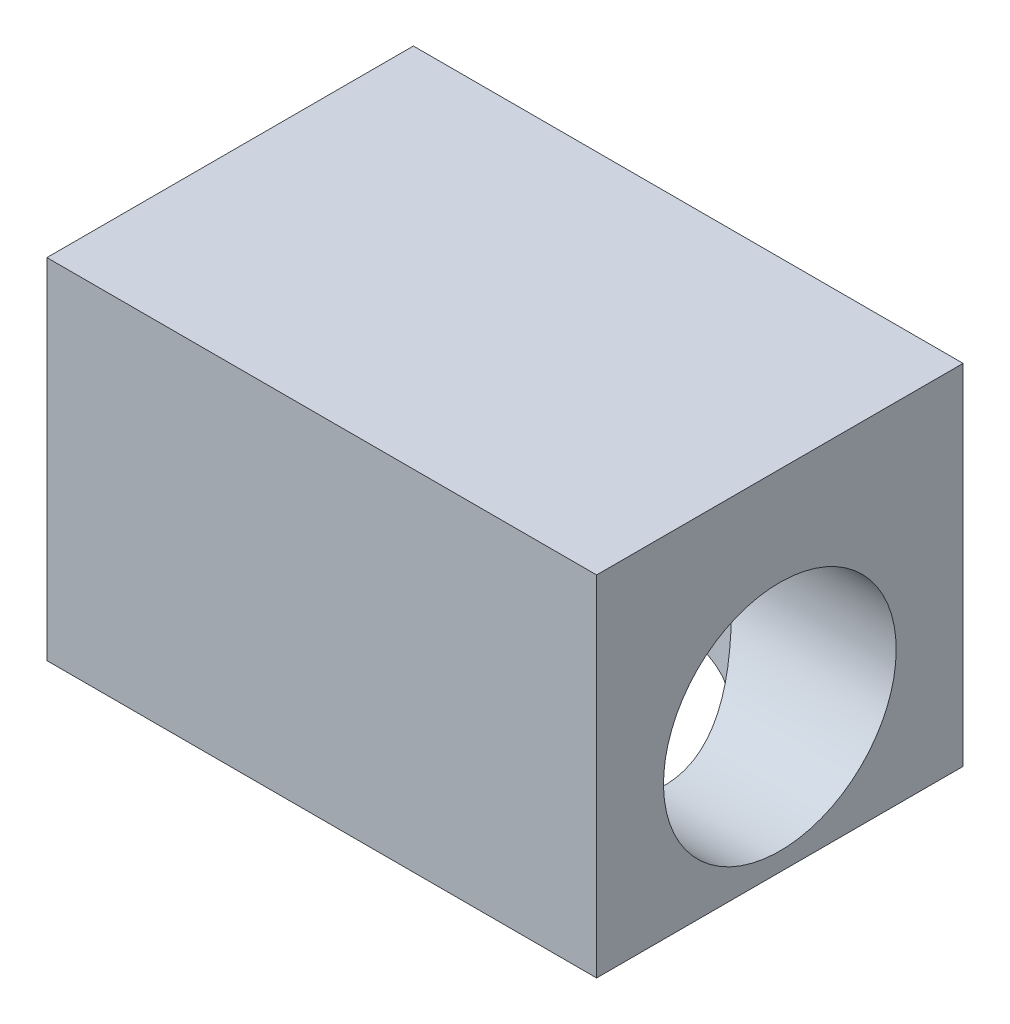
SolidWorks part; units mm, degrees
material "6061-T6 (SS)"
ref_plane "Front Plane" through (0, 0, 0) normal (0, 0, 1) x (1, 0, 0)
ref_plane "Top Plane" through (0, 0, 0) normal (0, 1, 0) x (1, 0, 0)
ref_plane "Right Plane" through (0, 0, 0) normal (1, 0, 0) x (0, 0, -1)
sketch "Sketch1" plane through (0, 0, 0) normal (0, 1, 0) x (1, 0, 0)
  line L1 (-30, 20) -> (30, 20)
  line L2 (-30, 20) -> (-30, -20)
  line L3 (-30, -20) -> (30, -20)
  line L4 (30, 20) -> (30, -20)
  line L5 (-30, 20) -> (30, -20) construction
  line L6 (-30, -20) -> (30, 20) construction
  point P0 (0, 0)
  dimension "D1" = 40
  dimension "D2" = 60
extrude "Boss-Extrude1" add sketch "Sketch1" against normal blind 38.1
sketch "Sketch2" plane through (0, 0, 0) normal (0, 0, 1) x (1, 0, 0)
  line L0 (62.6309, -36.1) -> (62.6309, -23.4)
  line L1 (62.6309, -23.4) -> (5, -23.4)
  line L2 (5, -23.4) -> (12.6309, -36.1)
  line L3 (12.6309, -36.1) -> (62.6309, -36.1)
  line L4 (0, 0) -> (0, -38.1) construction
  line L5 (-30, -38.1) -> (30, -38.1) construction
  line L6 (-12.6309, -36.1) -> (-5, -23.4)
  line L7 (-5, -23.4) -> (-62.6309, -23.4)
  line L8 (-62.6309, -23.4) -> (-62.6309, -36.1)
  line L9 (-62.6309, -36.1) -> (-12.6309, -36.1)
  line L10 (-5, -23.4) -> (5, -23.4) construction
  point P3 (37.6309, -36.1)
  point P10 (-13.5222, -2.3)
  point P11 (-5, -34.8708)
  point P16 (0, -23.4)
  point P17 (-11.2914, -2.3)
  point P18 (5, -17.5)
  point P19 (5, -20.6599)
  point P20 (-5, -34.9228)
  point P21 (-13.312, -35.9845)
  dimension "D1" = 12.7
  dimension "D2" = 121
  dimension "D3" = 10
  dimension "D4" = 50
  dimension "D5" = 2
revolve "Cut-Revolve1" cut sketch "Sketch2" angle 360 about L7
sketch "Sketch4" plane through (0, 0, 0) normal (0, 0, 1) x (1, 0, 0)
  line L0 (-17.5, -38.1) -> (-17.5, -11)
  line L1 (-30, -38.1) -> (30, -38.1) construction
  line L2 (-17.5, -11) -> (-13, -11)
  line L3 (-13, -11) -> (-13, -3)
  line L4 (-13, -3) -> (-11, -3)
  line L5 (-11, -3) -> (-11, -2)
  line L6 (-11, -2) -> (11, -2)
  line L7 (11, -2) -> (11, -3)
  line L8 (11, -3) -> (13, -3)
  line L9 (13, -3) -> (13, -11)
  line L10 (13, -11) -> (17.5, -11)
  line L11 (17.5, -11) -> (17.5, -38.1)
  line L12 (17.5, -38.1) -> (-17.5, -38.1)
  line L13 (0, -2) -> (0, -38.1)
  line L14 (-30, 0) -> (30, 0) construction
  point P16 (0, 0)
  point P20 (13, -3.4977)
  dimension "D1" = 35
  dimension "D2" = 26
  dimension "D3" = 22
  dimension "D4" = 1
  dimension "D5" = 2
  dimension "D6" = 8
revolve "Cut-Revolve2" cut sketch "Sketch4" angle 360 about L13
